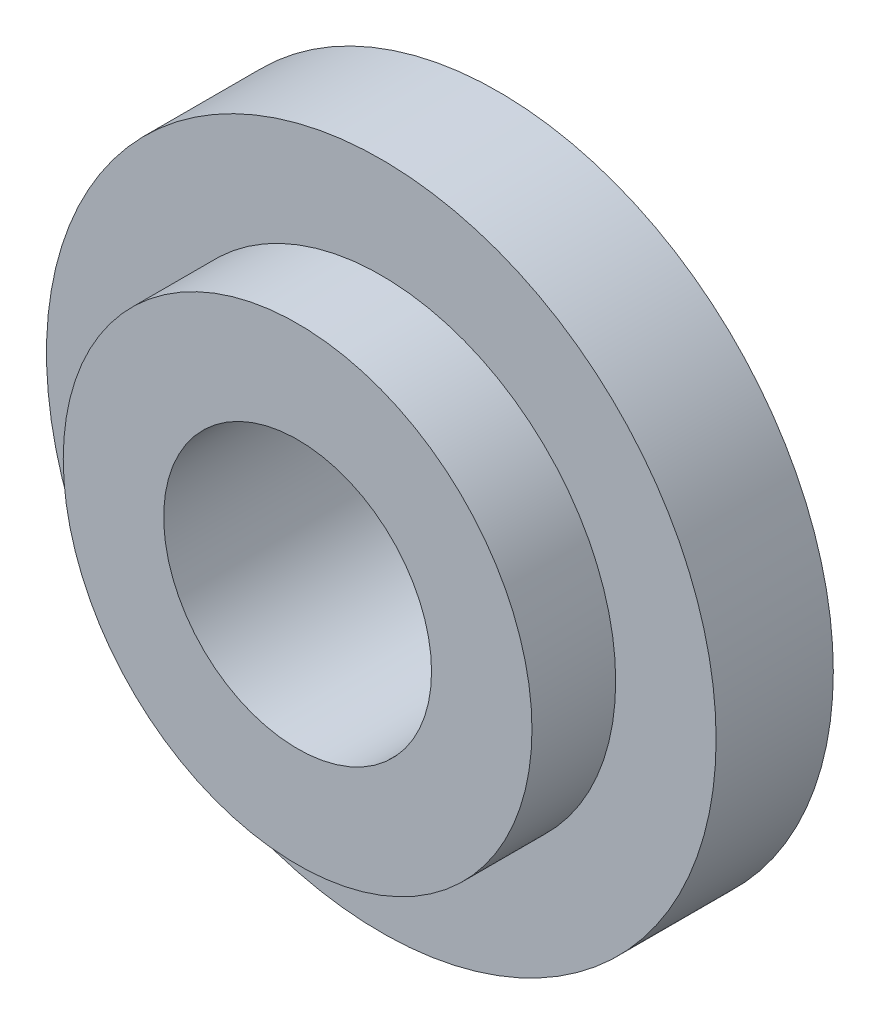
SolidWorks part; units mm, degrees
ref_plane "Plan1" through (0, 0, 0) normal (0, 0, 1) x (1, 0, 0)
ref_plane "Plan2" through (0, 0, 0) normal (0, 1, 0) x (1, 0, 0)
ref_plane "Plan3" through (0, 0, 0) normal (1, 0, 0) x (0, 0, -1)
sketch "Esquisse1" plane through (0, 0, 0) normal (0, 0, 1) x (1, 0, 0)
  circle A0 centre (0, 0) radius 10
  circle A1 centre (0, 0) radius 4
  dimension "D1" = 20
  dimension "D2" = 8
extrude "Base-Extrusion" add sketch "Esquisse1" along normal blind 3.5
sketch "Esquisse2" plane through (0, 0, 3.5) normal (0, 0, 1) x (1, 0, 0)
  circle A0 centre (0, 0) radius 7
  circle A1 centre (0, 0) radius 4
  dimension "D1" = 14
  dimension "D2" = 8
extrude "Boss.-Extru.1" add sketch "Esquisse2" along normal blind 2.5
